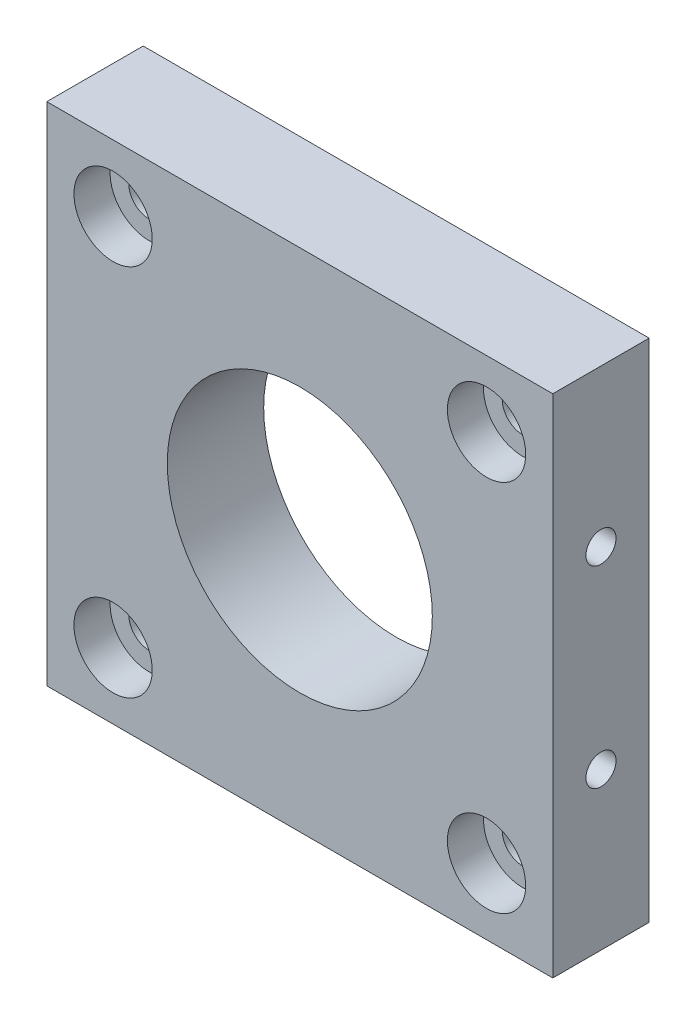
SolidWorks part; units mm, degrees
material "6061 合金"
ref_plane "前基準面" through (0, 0, 0) normal (0, 0, 1) x (1, 0, 0)
ref_plane "上基準面" through (0, 0, 0) normal (0, 1, 0) x (1, 0, 0)
ref_plane "右基準面" through (0, 0, 0) normal (1, 0, 0) x (0, 0, -1)
sketch "草圖1" plane through (0, 0, 0) normal (0, 0, 1) x (1, 0, 0)
  line L1 (-21, -21) -> (21, -21)
  line L2 (-21, -21) -> (-21, 21)
  line L3 (-21, 21) -> (21, 21)
  line L4 (21, -21) -> (21, 21)
  line L5 (-21, -21) -> (21, 21) construction
  line L6 (-21, 21) -> (21, -21) construction
  point P0 (0, 0)
  dimension "D1" = 42
  dimension "D2" = 42
extrude "填料-伸長1" add sketch "草圖1" along normal mid plane 8
sketch "草圖2" plane through (0, 0, 4) normal (0, 0, 1) x (1, 0, 0)
  circle A0 centre (0, 0) radius 11
  dimension "D1" = 22
extrude "除料-伸長1" cut sketch "草圖2" against normal through all
hole_wizard "M3 凹頭蓋螺釘的柱孔1" positions "草圖4" profile "草圖5" counterbore size "M3" standard "Ansi Metric" end condition through all
sketch "草圖4" plane through (0, 0, 4) normal (0, 0, 1) x (1, 0, 0)
  line L0 (-15.5, 15.5) -> (0, 15.5) construction
  line L1 (0, 15.5) -> (0, 0) construction
  point P0 (-15.5, 15.5)
  dimension "D1" = 15.5
  dimension "D2" = 15.5
sketch "草圖5" plane through (-15.5, 15.5, 4) normal (1, 0, 0) x (0, -1, 0)
  line L0 (0, 0) -> (0, 8)
  line L1 (0, 8) -> (1.7, 8)
  line L3 (1.7, 8) -> (1.7, 3)
  line L4 (1.7, 3) -> (3.25, 3)
  line L5 (3.25, 3) -> (3.25, 0)
  line L7 (3.25, 0) -> (0, 0)
  line L11 (0, -6.35) -> (0, 107.95) construction
  dimension "貫穿孔直徑" = 3.4
  dimension "貫穿孔深度" = 8
  dimension "柱孔直徑" = 6.5
  dimension "柱孔深度" = 3
pattern_circular "環狀複製排列1" count 4 over 360 about axis through (0, 0, 0) along (0, 0, 1) of "M3 凹頭蓋螺釘的柱孔1"
hole_wizard "M3x0.5 螺紋孔1" positions "草圖6" profile "草圖8" tap size "M3x0.5" standard "Ansi Metric"
sketch "草圖6" plane through (21, 0, 0) normal (1, 0, 0) x (0, 0, -1)
  line L2 (0, 8) -> (0, -8) construction
  point P4 (0, 8)
  point P5 (0, -8)
  dimension "D1" = 16
sketch "草圖8" plane through (21, 8, 0) normal (0, 1, 0) x (0, 0, -1)
  line L0 (0, 0) -> (0, 10.7511)
  line L1 (0, 10.7511) -> (1.25, 10)
  line L2 (1.25, 10) -> (1.25, 0)
  line L5 (1.25, 0) -> (0, 0)
  line L10 (0, 10.7511) -> (-1.25, 10) construction
  line L11 (0, -6.35) -> (0, 107.95) construction
  dimension "螺孔鑽直徑" = 2.5
  dimension "螺孔鑽深度" = 10
  dimension "導頭角度" = 118
